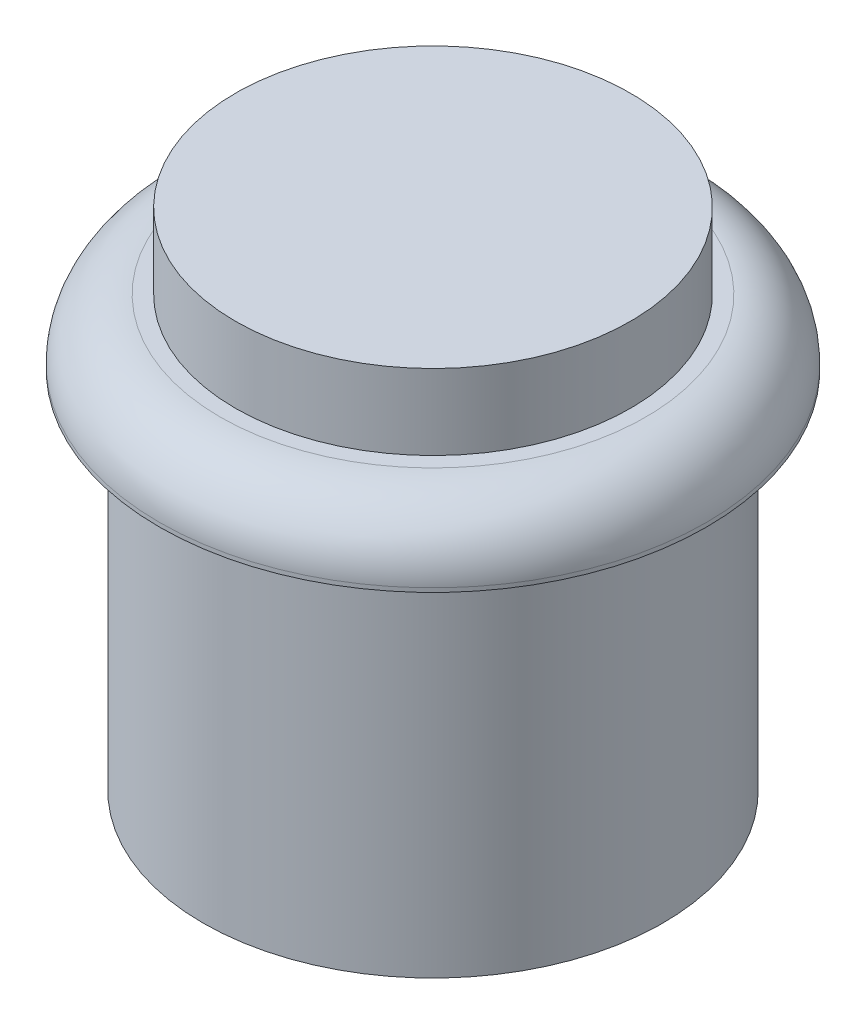
SolidWorks part; units mm, degrees
ref_plane "Front Plane" through (0, 0, 0) normal (0, 0, 1) x (1, 0, 0)
ref_plane "Top Plane" through (0, 0, 0) normal (0, 1, 0) x (1, 0, 0)
ref_plane "Right Plane" through (0, 0, 0) normal (1, 0, 0) x (0, 0, -1)
sketch "Sketch1" plane through (0, 0, 0) normal (0, 1, 0) x (1, 0, 0)
  circle A0 centre (0, 0) radius 11.35
  dimension "D1" = 22.7
extrude "Boss-Extrude1" add sketch "Sketch1" against normal blind 18
sketch "Sketch2" plane through (0, 0, 0) normal (0, 1, 0) x (1, 0, 0)
  circle A0 centre (0, 0) radius 13.5
  dimension "D1" = 27
extrude "Boss-Extrude2" add sketch "Sketch2" along normal blind 3.2
fillet "Fillet1" radius 3 1 edges at (0, 3.2, 13.5)
sketch "Sketch3" plane through (0, 3.2, 0) normal (0, 1, 0) x (1, 0, 0)
  circle A0 centre (0, 0) radius 9.75
  dimension "D1" = 19.5
extrude "Boss-Extrude3" add sketch "Sketch3" along normal blind 3.72
